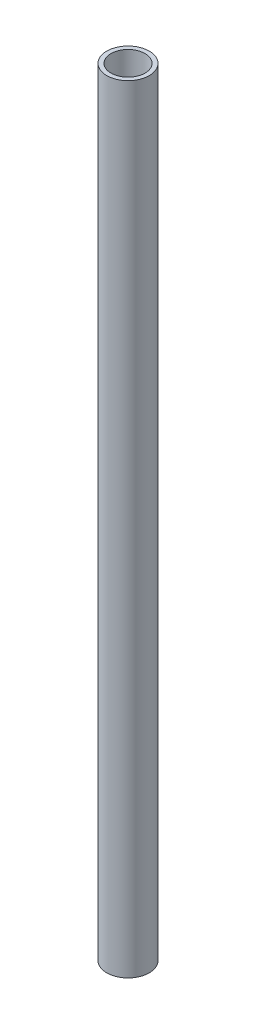
SolidWorks part; units mm, degrees
ref_plane "Front Plane" through (0, 0, 0) normal (0, 0, 1) x (1, 0, 0)
ref_plane "Top Plane" through (0, 0, 0) normal (0, 1, 0) x (1, 0, 0)
ref_plane "Right Plane" through (0, 0, 0) normal (1, 0, 0) x (0, 0, -1)
sketch "Sketch1" plane through (0, 0, 0) normal (0, 1, 0) x (1, 0, 0)
  circle A0 centre (0, 0) radius 20
  circle A1 centre (0, 0) radius 25
  dimension "D1" = 50
  dimension "D2" = 40
extrude "Boss-Extrude1" add sketch "Sketch1" along normal blind 914.4
